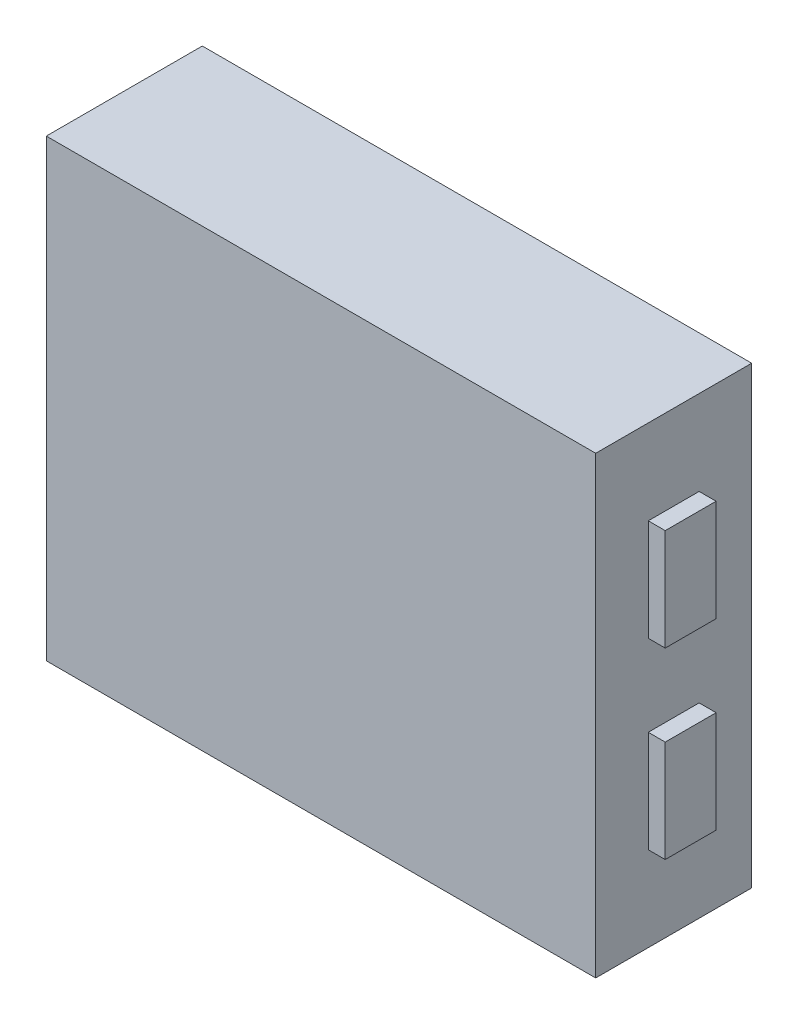
SolidWorks part; units mm, degrees
ref_plane "Plan de face" through (0, 0, 0) normal (0, 0, 1) x (1, 0, 0)
ref_plane "Plan de dessus" through (0, 0, 0) normal (0, 1, 0) x (1, 0, 0)
ref_plane "Plan de droite" through (0, 0, 0) normal (1, 0, 0) x (0, 0, -1)
sketch "Esquisse1" plane through (0, 0, 0) normal (0, 0, 1) x (1, 0, 0)
  line L1 (-48.7903, 31.1225) -> (113.2097, 31.1225)
  line L2 (-48.7903, 31.1225) -> (-48.7903, -102.8775)
  line L3 (-48.7903, -102.8775) -> (113.2097, -102.8775)
  line L4 (113.2097, 31.1225) -> (113.2097, -102.8775)
  dimension "D1" = 162
  dimension "D2" = 134
extrude "Boss.-Extru.1" add sketch "Esquisse1" along normal blind 46
sketch "Esquisse2" plane through (113.2097, 0, 0) normal (1, 0, 0) x (0, 0, -1)
  line L0 (-46, -102.8775) -> (-46, 31.1225) construction
  line L1 (-30.5, 6.1225) -> (-15.5, 6.1225)
  line L2 (-30.5, 6.1225) -> (-30.5, -23.8775)
  line L3 (-30.5, -23.8775) -> (-15.5, -23.8775)
  line L4 (-15.5, 6.1225) -> (-15.5, -23.8775)
  line L5 (-30.5, 6.1225) -> (-15.5, -23.8775) construction
  line L6 (-30.5, -23.8775) -> (-15.5, 6.1225) construction
  line L7 (-46, -35.8775) -> (0, -35.8775) construction
  line L8 (0, -102.8775) -> (0, 31.1225) construction
  line L9 (-30.5, -47.8775) -> (-15.5, -47.8775)
  line L10 (-15.5, -77.8775) -> (-15.5, -47.8775)
  line L11 (-30.5, -77.8775) -> (-15.5, -77.8775)
  line L12 (-30.5, -77.8775) -> (-30.5, -47.8775)
  line L13 (-46, 31.1225) -> (0, 31.1225) construction
  point P0 (-23, -8.8775)
  dimension "D1" = 30
  dimension "D2" = 15
  dimension "D3" = 23
  dimension "D4" = 40
extrude "Boss.-Extru.2" add sketch "Esquisse2" along normal blind 5
